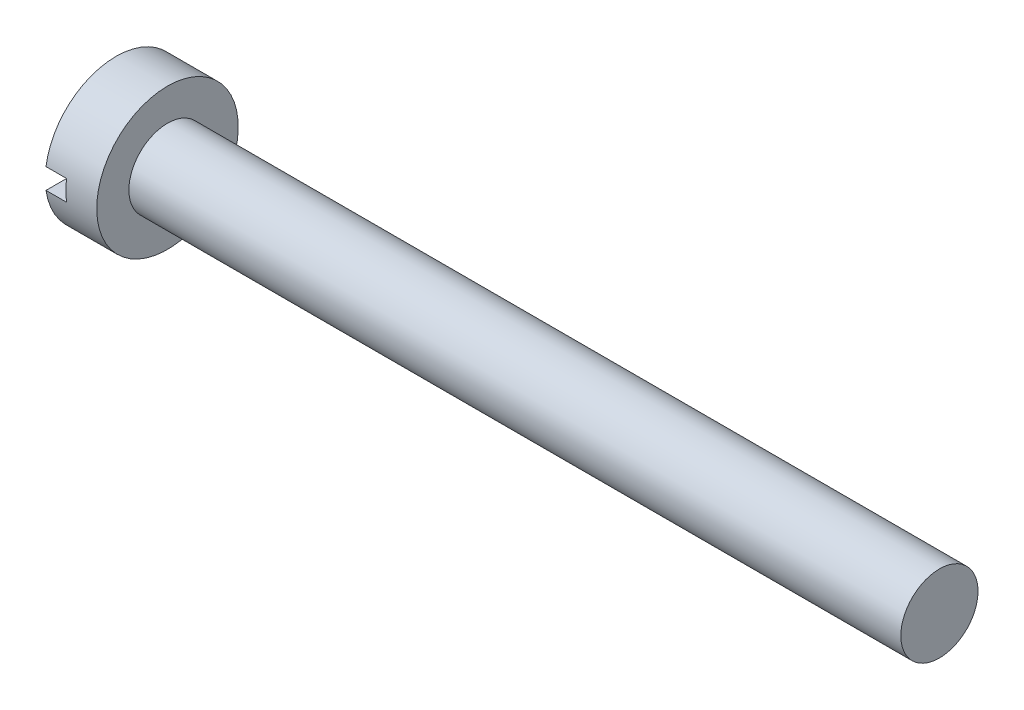
SolidWorks part; units mm, degrees
material "Plain Carbon Steel"
ref_plane "Front Plane" through (0, 0, 0) normal (0, 0, 1) x (1, 0, 0)
ref_plane "Top Plane" through (0, 0, 0) normal (0, 1, 0) x (1, 0, 0)
ref_plane "Right Plane" through (0, 0, 0) normal (1, 0, 0) x (0, 0, -1)
sketch "Sketch1" plane through (0, 0, 0) normal (0, 0, 1) x (1, 0, 0)
  line L0 (0, 0) -> (0, 2.75)
  line L1 (0, 2.75) -> (2, 2.75)
  line L2 (2, 2.75) -> (2, 1.5)
  line L3 (2, 1.5) -> (32, 1.5)
  line L4 (32, 1.5) -> (32, 0)
  line L5 (32, 0) -> (0, 0) construction
  line L6 (0, 0) -> (32, 0)
  dimension "D1" = 3
  dimension "D2" = 30
  dimension "D3" = 5.5
  dimension "D4" = 2
revolve "Revolve1" add sketch "Sketch1" angle 360 about L5
sketch "Sketch2" plane through (0, 0, 0) normal (-1, 0, 0) x (0, 0, 1)
  line L0 (2.75, 0) -> (-2.75, 0) construction
  line L1 (-2.75, 0.4) -> (2.75, 0.4)
  line L2 (-2.75, 0.4) -> (-2.75, -0.4)
  line L3 (-2.75, -0.4) -> (2.75, -0.4)
  line L4 (2.75, 0.4) -> (2.75, -0.4)
  circle A0 centre (0, 0) radius 2.75 construction
  dimension "D1" = 0.8
extrude "Cut-Extrude1" cut sketch "Sketch2" against normal blind 0.8
